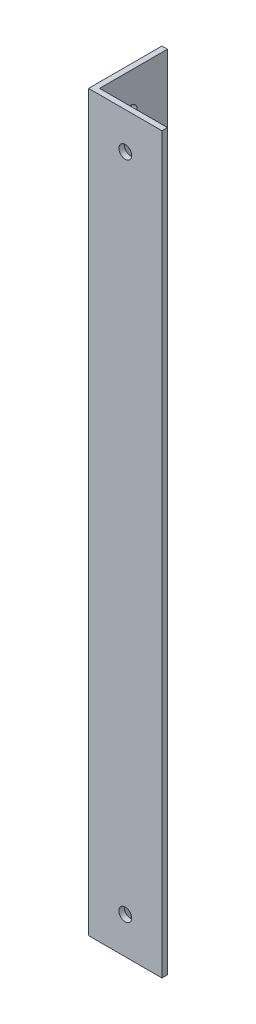
SolidWorks part; units mm, degrees
material "1060 Сплав"
ref_plane "Спереди" through (0, 0, 0) normal (0, 0, 1) x (1, 0, 0)
ref_plane "Сверху" through (0, 0, 0) normal (0, 1, 0) x (1, 0, 0)
ref_plane "Справа" through (0, 0, 0) normal (1, 0, 0) x (0, 0, -1)
sketch "Эскиз1" plane through (0, 0, 0) normal (0, 1, 0) x (1, 0, 0)
  line L0 (0, 0) -> (20, 0)
  line L1 (20, 0) -> (20, 1.5)
  line L2 (20, 1.5) -> (1.5, 1.5)
  line L3 (1.5, 1.5) -> (1.5, 20)
  line L4 (1.5, 20) -> (0, 20)
  line L5 (0, 20) -> (0, 0)
  dimension "D1" = 20
  dimension "D2" = 1.5
extrude "Бобышка-Вытянуть1" add sketch "Эскиз1" along normal blind 200
sketch "Эскиз2" plane through (0, 0, 0) normal (0, 0, 1) x (1, 0, 0)
  line L0 (0, 200) -> (20, 200) construction
  circle A0 centre (10, 190) radius 1.75
  point P4 (10, 200)
  dimension "D1" = 3.5
  dimension "D2" = 10
extrude "Вырез-Вытянуть1" cut sketch "Эскиз2" against normal up to next
ref_plane "Плоскость1" through (0, 0, 0) normal (-0.7071, 0, -0.7071) x (-0.7071, 0, 0.7071)
ref_plane "Плоскость2" through (0, 100, 0) normal (0, -1, 0) x (-1, 0, 0)
mirror "Зеркальное отражение1" about plane through (0, 0, 0) normal (-0.7071, 0, -0.7071) of "Вырез-Вытянуть1"
mirror "Зеркальное отражение2" about plane through (0, 100, 0) normal (0, -1, 0) of "Зеркальное отражение1", "Вырез-Вытянуть1"
equation "\"ATX.Case.01.Dimension.3\"=200"
equation "\"ATX.Case.01.Profile.20.Width\"=20"
equation "\"ATX.Case.01.Profile.20.Thickness\" = 1.5"
equation "\"D1@Эскиз1\"= \"ATX.Case.01.Profile.20.Width\""
equation "\"D2@Эскиз1\"= \"ATX.Case.01.Profile.20.Thickness\""
equation "\"D1@Бобышка-Вытянуть1\"= \"ATX.Case.01.Dimension.3\""
equation "\"D2@Эскиз2\"= \"ATX.Case.01.Profile.20.Width\" / 2"
